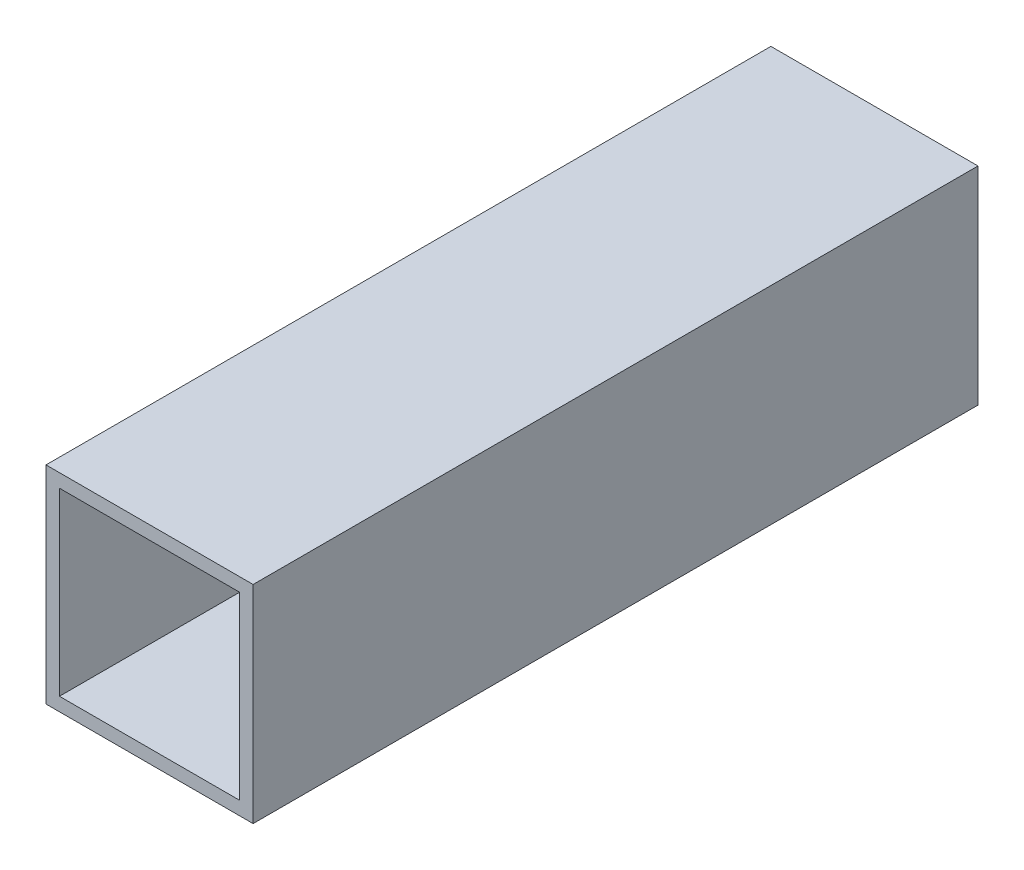
SolidWorks part; units mm, degrees
ref_plane "Front Plane" through (0, 0, 0) normal (0, 0, 1) x (1, 0, 0)
ref_plane "Top Plane" through (0, 0, 0) normal (0, 1, 0) x (1, 0, 0)
ref_plane "Right Plane" through (0, 0, 0) normal (1, 0, 0) x (0, 0, -1)
sketch "Sketch1" plane through (0, 0, 0) normal (0, 0, 1) x (1, 0, 0)
  line L1 (-58.5076, -35.6476) -> (-33.1076, -35.6476)
  line L2 (-58.5076, -35.6476) -> (-58.5076, -10.2476)
  line L3 (-58.5076, -10.2476) -> (-33.1076, -10.2476)
  line L4 (-33.1076, -35.6476) -> (-33.1076, -10.2476)
  dimension "D1" = 25.4
  dimension "D2" = 25.4
extrude "Boss-Extrude1" add sketch "Sketch1" along normal blind 88.9
sketch "Sketch2" plane through (0, 0, 88.9) normal (0, 0, 1) x (1, 0, 0)
  line L0 (-58.5076, -10.2476) -> (-58.5076, -35.6476) construction
  line L1 (-56.8566, -11.8986) -> (-34.7586, -11.8986)
  line L2 (-56.8566, -11.8986) -> (-56.8566, -33.9966)
  line L3 (-56.8566, -33.9966) -> (-34.7586, -33.9966)
  line L4 (-34.7586, -11.8986) -> (-34.7586, -33.9966)
  line L5 (-56.8566, -11.8986) -> (-34.7586, -33.9966) construction
  line L6 (-56.8566, -33.9966) -> (-34.7586, -11.8986) construction
  line L7 (-33.1076, -10.2476) -> (-58.5076, -10.2476) construction
  line L8 (-33.1076, -35.6476) -> (-33.1076, -10.2476) construction
  line L9 (-58.5076, -35.6476) -> (-33.1076, -35.6476) construction
  point P0 (-45.8076, -22.9476)
  dimension "D1" = 1.651
  dimension "D2" = 1.651
  dimension "D3" = 1.651
  dimension "D4" = 1.651
extrude "Cut-Extrude1" cut sketch "Sketch2" against normal through all
